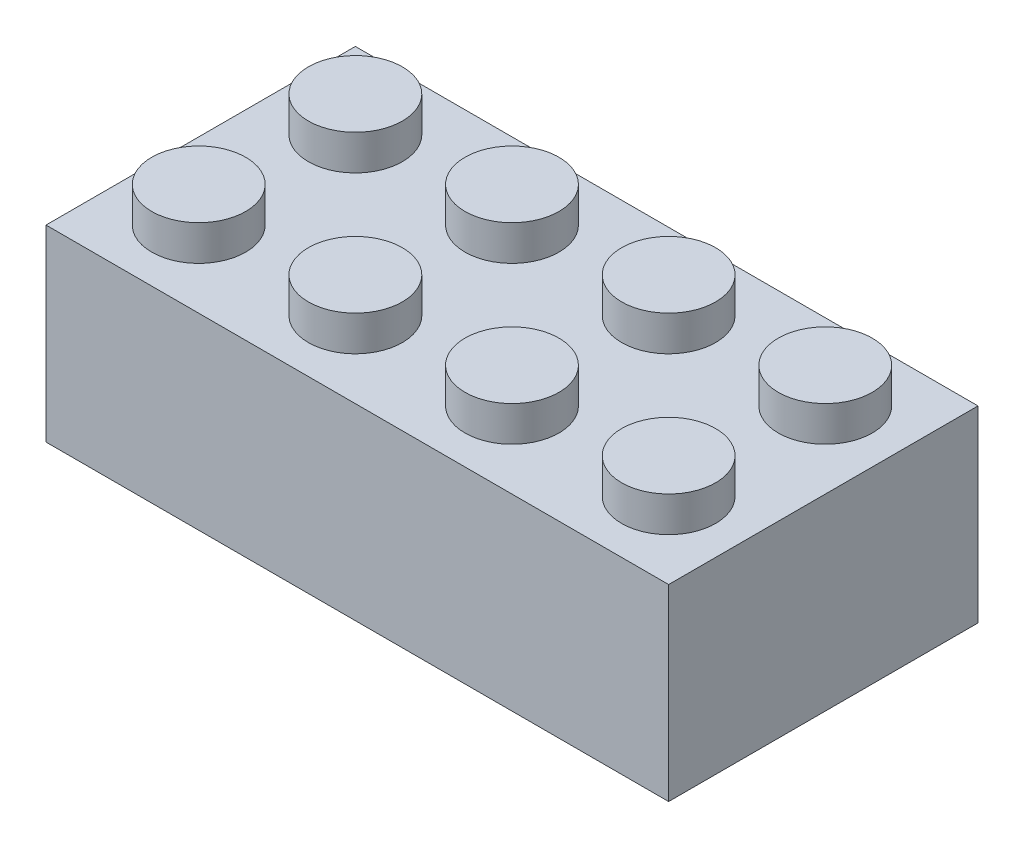
SolidWorks part; units mm, degrees
ref_plane "Front Plane" through (0, 0, 0) normal (0, 0, 1) x (1, 0, 0)
ref_plane "Top Plane" through (0, 0, 0) normal (0, 1, 0) x (1, 0, 0)
ref_plane "Right Plane" through (0, 0, 0) normal (1, 0, 0) x (0, 0, -1)
sketch "Sketch1" plane through (0, 0, 0) normal (0, 1, 0) x (1, 0, 0)
  line L0 (126.6534, 491.0116) -> (1228.6534, 491.0116) construction
  line L1 (15.9, -7.9) -> (-15.9, -7.9)
  line L2 (15.9, -7.9) -> (15.9, 7.9)
  line L3 (15.9, 7.9) -> (-15.9, 7.9)
  line L4 (-15.9, -7.9) -> (-15.9, 7.9)
  line L5 (0, 19.833) -> (0, -12.0961) construction
  line L6 (-12.3, -6.7) -> (-14.7, -6.7)
  line L7 (14.7, 6.7) -> (12.3, 6.7)
  line L8 (-14.7, -6.7) -> (-14.7, -4.3)
  line L9 (14.7, -6.7) -> (12.3, -6.7)
  line L10 (14.7, -6.7) -> (14.7, -4.3)
  line L11 (-19.6742, 0) -> (21.284, 0) construction
  line L12 (-12.3, -6.5) -> (-11.7, -6.5)
  line L13 (-12.3, -6.5) -> (-12.3, -6.7)
  line L14 (-11.7, -6.5) -> (-11.7, -6.7)
  line L15 (14.7, -6.7) -> (-14.7, -6.7) construction
  line L16 (-4.3, -6.5) -> (-4.3, -6.7)
  line L17 (-4.3, -6.5) -> (-3.7, -6.5)
  line L18 (-3.7, -6.5) -> (-3.7, -6.7)
  line L19 (3.7, -6.5) -> (3.7, -6.7)
  line L20 (3.7, -6.5) -> (4.3, -6.5)
  line L21 (4.3, -6.5) -> (4.3, -6.7)
  line L22 (11.7, -6.5) -> (11.7, -6.7)
  line L23 (11.7, -6.5) -> (12.3, -6.5)
  line L24 (12.3, -6.5) -> (12.3, -6.7)
  line L25 (-4.3, -6.7) -> (-11.7, -6.7)
  line L26 (3.7, -6.7) -> (-3.7, -6.7)
  line L27 (11.7, -6.7) -> (4.3, -6.7)
  line L28 (12.3, 6.5) -> (12.3, 6.7)
  line L29 (11.7, 6.5) -> (12.3, 6.5)
  line L30 (11.7, 6.5) -> (11.7, 6.7)
  line L31 (4.3, 6.5) -> (4.3, 6.7)
  line L32 (3.7, 6.5) -> (4.3, 6.5)
  line L33 (3.7, 6.5) -> (3.7, 6.7)
  line L34 (-3.7, 6.5) -> (-3.7, 6.7)
  line L35 (-4.3, 6.5) -> (-3.7, 6.5)
  line L36 (-4.3, 6.5) -> (-4.3, 6.7)
  line L37 (-11.7, 6.5) -> (-11.7, 6.7)
  line L38 (-12.3, 6.5) -> (-11.7, 6.5)
  line L39 (-12.3, 6.5) -> (-12.3, 6.7)
  line L40 (-12.3, 6.7) -> (-14.7, 6.7)
  line L41 (14.7, 6.7) -> (-14.7, 6.7) construction
  line L42 (-4.3, 6.7) -> (-11.7, 6.7)
  line L43 (3.7, 6.7) -> (-3.7, 6.7)
  line L44 (11.7, 6.7) -> (4.3, 6.7)
  line L45 (-14.5, -3.7) -> (-14.7, -3.7)
  line L46 (-14.5, 4.3) -> (-14.5, 3.7)
  line L47 (-14.5, 3.7) -> (-14.7, 3.7)
  line L48 (-14.5, 4.3) -> (-14.7, 4.3)
  line L49 (-14.7, 4.3) -> (-14.7, 6.7)
  line L50 (-14.7, -6.7) -> (-14.7, 6.7) construction
  line L51 (-14.5, -4.3) -> (-14.5, -3.7)
  line L52 (-14.5, -4.3) -> (-14.7, -4.3)
  line L53 (-14.7, -3.7) -> (-14.7, 3.7)
  line L54 (14.5, 3.7) -> (14.7, 3.7)
  line L55 (14.5, 4.3) -> (14.5, 3.7)
  line L56 (14.5, 4.3) -> (14.7, 4.3)
  line L57 (14.5, -4.3) -> (14.7, -4.3)
  line L58 (14.5, -3.7) -> (14.7, -3.7)
  line L59 (14.5, -3.7) -> (14.5, -4.3)
  line L60 (14.7, 4.3) -> (14.7, 6.7)
  line L61 (14.7, -6.7) -> (14.7, 6.7) construction
  line L62 (14.7, -3.7) -> (14.7, 3.7)
  point P0 (0, 0)
  point P17 (-12, 0)
  point P70 (-14.5, 4)
  dimension "D2" = 4
  dimension "D1" = 1.2
extrude "Boss-Extrude1" add sketch "Sketch1" along normal blind 9.6
sketch "Sketch3" plane through (0, 9.6, 0) normal (0, 1, 0) x (1, 0, 0)
  line L1 (-15.9, -7.9) -> (15.9, -7.9)
  line L2 (-15.9, -7.9) -> (-15.9, 7.9)
  line L3 (-15.9, 7.9) -> (15.9, 7.9)
  line L4 (15.9, -7.9) -> (15.9, 7.9)
  line L5 (-15.9, -7.9) -> (15.9, 7.9) construction
  line L6 (-15.9, 7.9) -> (15.9, -7.9) construction
  point P0 (0, 0)
extrude "Boss-Extrude2" add sketch "Sketch3" against normal blind 1
sketch "Sketch4" plane through (0, 9.6, 0) normal (0, 1, 0) x (1, 0, 0)
  circle A0 centre (-12, 4) radius 2.4
  circle A1 centre (-4, 4) radius 2.4
  circle A2 centre (4, 4) radius 2.4
  circle A3 centre (12, 4) radius 2.4
  circle A4 centre (-12, -4) radius 2.4
  circle A5 centre (-4, -4) radius 2.4
  circle A6 centre (4, -4) radius 2.4
  circle A7 centre (12, -4) radius 2.4
  dimension "D1" = 8
  dimension "D2" = 8
extrude "Boss-Extrude3" add sketch "Sketch4" along normal blind 1.8
sketch "Sketch5" plane through (0, 8.6, 0) normal (0, -1, 0) x (1, 0, 0)
  circle A0 centre (12, -4) radius 1.3
  circle A1 centre (12, 4) radius 1.3
  circle A2 centre (4, -4) radius 1.3
  circle A3 centre (4, 4) radius 1.3
  circle A4 centre (-4, 4) radius 1.3
  circle A5 centre (-4, -4) radius 1.3
  circle A6 centre (-12, -4) radius 1.3
  circle A7 centre (-12, 4) radius 1.3
extrude "Cut-Extrude1" cut sketch "Sketch5" against normal blind 1.7
sketch "Sketch6" plane through (0, 8.6, 0) normal (0, -1, 0) x (1, 0, 0)
  line L0 (0, -19.833) -> (0, 12.0961) construction
  line L2 (-19.6742, 0) -> (21.284, 0) construction
  circle A0 centre (8, 0) radius 2.4
  circle A1 centre (8, 0) radius 3.255
  circle A2 centre (-8, 0) radius 3.255
  circle A3 centre (-8, 0) radius 2.4
  circle A4 centre (0, 0) radius 2.4
  circle A5 centre (0, 0) radius 3.225
  dimension "D1" = 6.51
  dimension "D2" = 8
extrude "Boss-Extrude4" add sketch "Sketch6" along normal up to surface (8.6 mm away) up to face at (0, 0, 0)
sketch "Sketch7" plane through (0, 8.6, 0) normal (0, -1, 0) x (1, 0, 0)
  line L0 (0.4, -6.7) -> (-0.4, -6.7)
  line L1 (3.7, -6.7) -> (-3.7, -6.7) construction
  line L2 (0.4, 6.7) -> (-0.4, 6.7)
  line L3 (3.7, 6.7) -> (-3.7, 6.7) construction
  line L4 (0.4, -6.7) -> (0.4, -2.9407)
  line L5 (0.4, -2.9407) -> (-0.4, -2.9407)
  line L6 (-0.4, -2.9407) -> (-0.4, -6.7)
  line L7 (0.4, 6.7) -> (0.4, 2.8591)
  line L8 (0.4, 2.8591) -> (-0.4, 2.8591)
  line L9 (-0.4, 2.8591) -> (-0.4, 6.7)
  point P5 (0, -6.7)
  point P10 (0, 6.7)
extrude "Boss-Extrude5" add sketch "Sketch7" along normal blind 6.3
